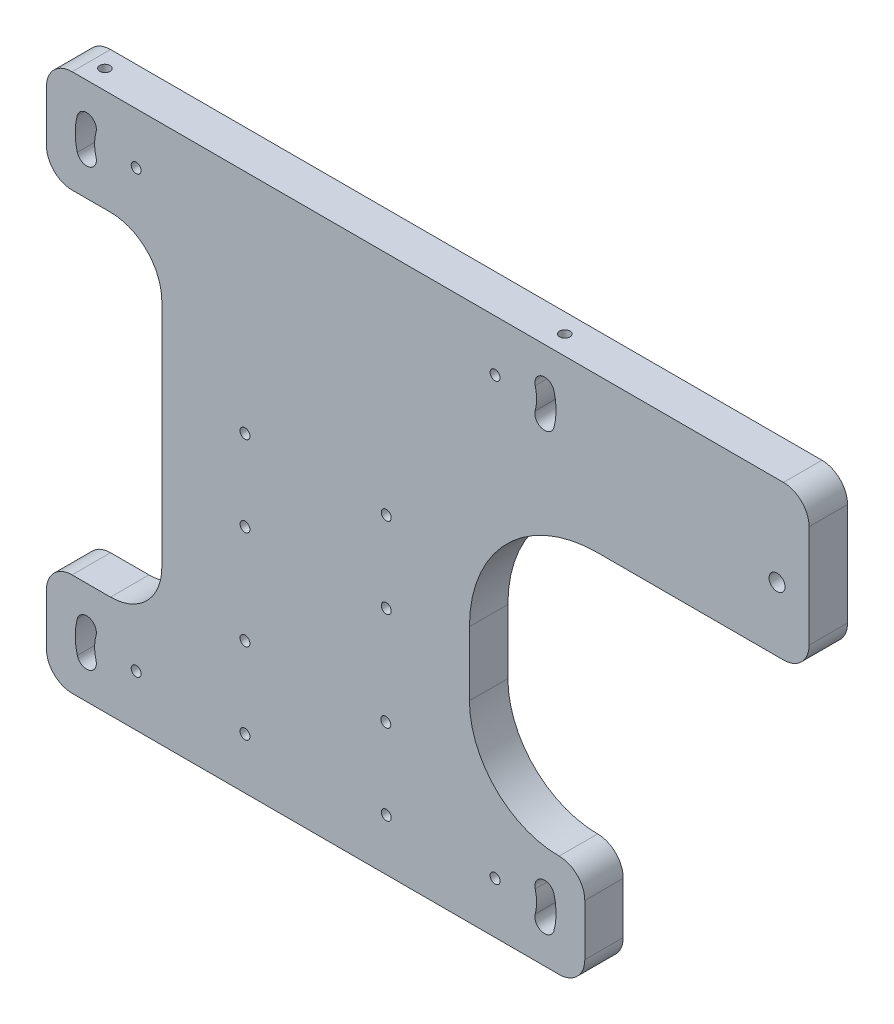
SolidWorks part; units mm, degrees
ref_plane "Front Plane" through (0, 0, 0) normal (0, 0, 1) x (1, 0, 0)
ref_plane "Top Plane" through (0, 0, 0) normal (0, 1, 0) x (1, 0, 0)
ref_plane "Right Plane" through (0, 0, 0) normal (1, 0, 0) x (0, 0, -1)
sketch "Model" plane through (0, 0, 0) normal (0, 0, 1) x (1, 0, 0)
  line L0 (785.5248, 413.0727) -> (433.0998, 413.0727)
  line L1 (798.2248, 349.5727) -> (798.2248, 400.3727)
  line L2 (693.4498, 336.8727) -> (785.5248, 336.8727)
  line L3 (629.9498, 241.6227) -> (629.9498, 273.3727)
  line L4 (687.0998, 159.0727) -> (687.0998, 184.4727)
  line L5 (433.0998, 146.3727) -> (674.3998, 146.3727)
  line L6 (420.3998, 184.4727) -> (420.3998, 159.0727)
  line L7 (452.1498, 197.1727) -> (433.0998, 197.1727)
  line L8 (477.5498, 336.8727) -> (477.5498, 222.5727)
  line L9 (433.0998, 362.2727) -> (452.1498, 362.2727)
  line L10 (420.3998, 400.3727) -> (420.3998, 374.9727)
  arc A0 (444.9702, 177.1675) -> (444.9702, 166.378) centre (465.1038, 171.7727) ccw
  arc A1 (444.9702, 177.1675) -> (435.6778, 179.6574) centre (440.324, 178.4125) ccw
  arc A2 (435.6778, 179.6574) -> (435.6778, 163.8881) centre (465.1038, 171.7727) ccw
  arc A3 (435.6778, 163.8881) -> (444.9702, 166.378) centre (440.324, 165.133) ccw
  arc A4 (671.8219, 163.8881) -> (671.8219, 179.6574) centre (642.3958, 171.7727) ccw
  arc A5 (671.8219, 179.6574) -> (662.5295, 177.1675) centre (667.1757, 178.4125) ccw
  arc A6 (662.5295, 166.378) -> (662.5295, 177.1675) centre (642.3958, 171.7727) ccw
  arc A7 (662.5295, 166.378) -> (671.8219, 163.8881) centre (667.1757, 165.133) ccw
  circle A8 centre (518.7498, 171.7727) radius 2.4574
  circle A9 centre (588.5264, 211.7727) radius 2.4574
  circle A10 centre (518.7498, 260.6727) radius 2.4574
  circle A11 centre (588.7498, 300.6727) radius 2.4574
  circle A12 centre (782.3498, 368.6168) radius 3.9688
  circle A13 centre (642.6498, 171.7727) radius 2.4574
  circle A14 centre (464.8498, 171.7727) radius 2.4575
  arc A15 (798.2248, 400.3727) -> (785.5248, 413.0727) centre (785.5248, 400.3727) ccw
  arc A16 (785.5248, 336.8727) -> (798.2248, 349.5727) centre (785.5248, 349.5727) ccw
  arc A17 (693.4498, 336.8727) -> (629.9498, 273.3727) centre (693.4498, 273.3727) ccw
  arc A18 (629.9498, 241.6227) -> (674.3998, 197.1727) centre (674.3998, 241.6227) ccw
  arc A19 (687.0998, 184.4727) -> (674.3998, 197.1727) centre (674.3998, 184.4727) ccw
  arc A20 (674.3998, 146.3727) -> (687.0998, 159.0727) centre (674.3998, 159.0727) ccw
  arc A21 (420.3998, 159.0727) -> (433.0998, 146.3727) centre (433.0998, 159.0727) ccw
  arc A22 (433.0998, 197.1727) -> (420.3998, 184.4727) centre (433.0998, 184.4727) ccw
  arc A23 (452.1498, 197.1727) -> (477.5498, 222.5727) centre (452.1498, 222.5727) ccw
  arc A24 (477.5498, 336.8727) -> (452.1498, 362.2727) centre (452.1498, 336.8727) ccw
  arc A25 (420.3998, 374.9727) -> (433.0998, 362.2727) centre (433.0998, 374.9727) ccw
  arc A26 (433.0998, 413.0727) -> (420.3998, 400.3727) centre (433.0998, 400.3727) ccw
  circle A27 centre (464.8498, 387.6727) radius 2.4575
  circle A28 centre (642.6498, 387.6727) radius 2.4575
  circle A29 centre (518.7498, 300.6727) radius 2.4574
  circle A30 centre (588.7498, 260.6727) radius 2.4574
  circle A31 centre (518.7498, 211.7727) radius 2.4574
  circle A32 centre (588.7498, 171.9962) radius 2.4574
  arc A33 (671.8219, 379.7881) -> (671.8219, 395.5574) centre (642.3958, 387.6727) ccw
  arc A34 (671.8219, 395.5574) -> (662.5295, 393.0675) centre (667.1757, 394.3125) ccw
  arc A35 (662.5295, 382.278) -> (662.5295, 393.0675) centre (642.3958, 387.6727) ccw
  arc A36 (662.5295, 382.278) -> (671.8219, 379.7881) centre (667.1757, 381.033) ccw
  arc A37 (444.9702, 393.0675) -> (444.9702, 382.278) centre (465.1038, 387.6727) ccw
  arc A38 (444.9702, 393.0675) -> (435.6778, 395.5574) centre (440.324, 394.3125) ccw
  arc A39 (435.6778, 395.5574) -> (435.6778, 379.7881) centre (465.1038, 387.6727) ccw
  arc A40 (435.6778, 379.7881) -> (444.9702, 382.278) centre (440.324, 381.033) ccw
extrude "Boss-Extrude1" add sketch "Model" along normal blind 19.05
sketch "Sketch2" plane through (0, 146.3727, 0) normal (0, -1, 0) x (1, 0, 0)
  line L0 (687.0998, 9.525) -> (420.3998, 9.525) construction
  line L1 (687.0998, 19.05) -> (687.0998, 0) construction
  line L2 (420.3998, 19.05) -> (420.3998, 0) construction
  line L3 (420.3998, 9.525) -> (687.0998, 9.525) construction
  line L4 (553.7498, 19.05) -> (553.7498, 0) construction
  line L5 (433.0998, 19.05) -> (674.3998, 19.05) construction
  line L6 (433.0998, 0) -> (674.3998, 0) construction
  circle A0 centre (439.8308, 9.525) radius 2.5527
  circle A1 centre (667.6688, 9.525) radius 2.5527
  dimension "D1" = 5.1054
  dimension "D2" = 19.431
extrude "Cut-Extrude1" cut sketch "Sketch2" against normal up to next
sketch "Sketch4" plane through (0, 413.0727, 0) normal (0, 1, 0) x (1, 0, 0)
  line L0 (667.6688, -9.525) -> (439.8308, -9.525) construction
  line L1 (553.7498, -19.05) -> (553.7498, 0) construction
  line L2 (785.5248, -19.05) -> (433.0998, -19.05) construction
  line L3 (785.5248, 0) -> (433.0998, 0) construction
  circle A0 centre (439.8308, -9.525) radius 2.5527
  circle A1 centre (667.6688, -9.525) radius 2.5527
  dimension "D1" = 5.1054
extrude "Cut-Extrude2" cut sketch "Sketch4" against normal up to next
